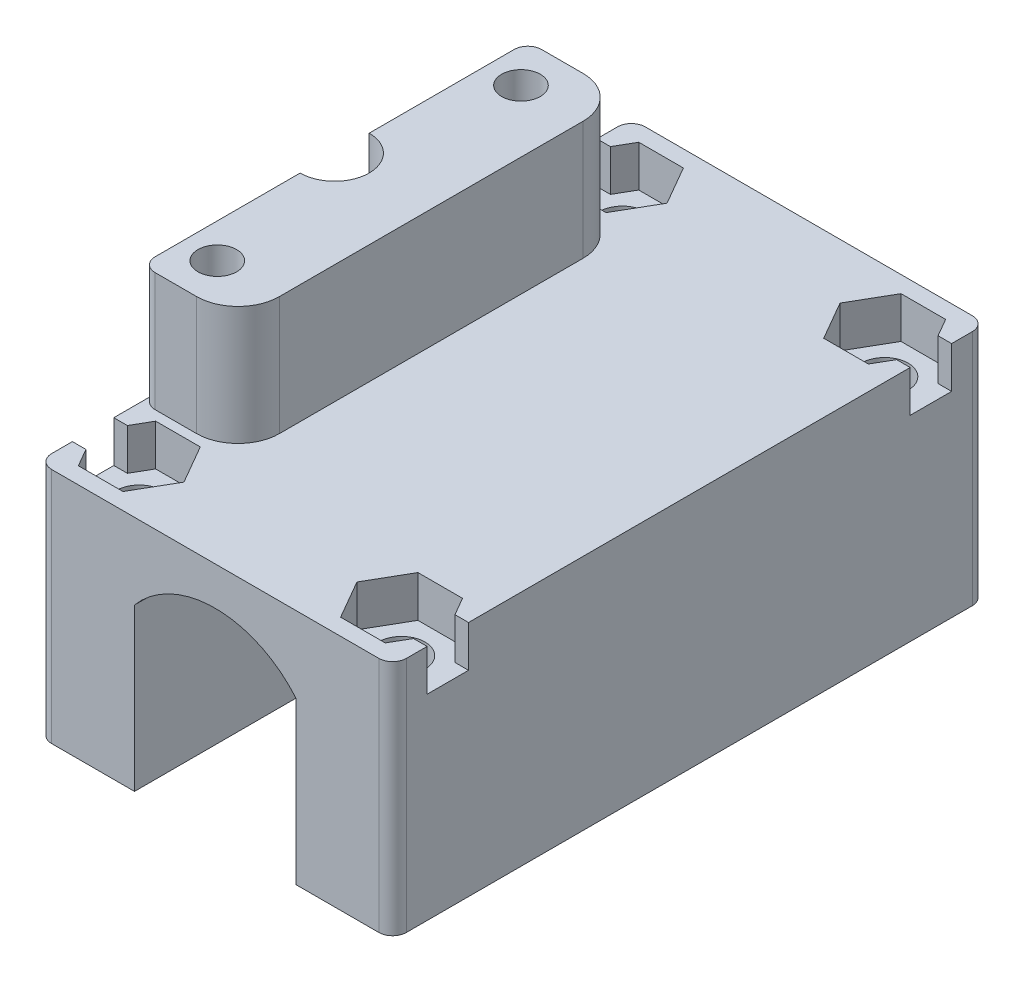
SolidWorks part; units mm, degrees
material "ABS"
ref_plane "Front" through (0, 0, 0) normal (0, 0, 1) x (1, 0, 0)
ref_plane "Top" through (0, 0, 0) normal (0, 1, 0) x (1, 0, 0)
ref_plane "Right" through (0, 0, 0) normal (1, 0, 0) x (0, 0, -1)
sketch "Эскиз1" plane through (0, 0, 0) normal (0, 0, 1) x (1, 0, 0)
  line L0 (0, 0) -> (0, 2.2539) construction
  line L1 (0, 0) -> (0, 23.5957) construction
  line L2 (5.85, 0) -> (5.85, 11.6995)
  line L3 (-12.85, 17.2) -> (12.85, 17.2)
  line L4 (12.85, 17.2) -> (12.85, 0)
  line L5 (12.85, 0) -> (5.85, 0)
  line L6 (-12.85, 0) -> (-5.85, 0)
  line L7 (-12.85, 17.2) -> (-12.85, 0)
  line L8 (-5.85, 0) -> (-5.85, 11.6995)
  arc A0 (5.85, 11.6995) -> (-5.85, 11.6995) centre (0, 6.77) ccw
  point P15 (0, 17.2)
  dimension "D3" = 6.77
  dimension "D4" = 15.3
  dimension "D1" = 11.7
  dimension "D5" = 7
  dimension "D6" = 17.2
extrude "Бобышка-Вытянуть1" add sketch "Эскиз1" along normal blind 43
sketch "Эскиз2" plane through (0, 17.2, 0) normal (0, 1, 0) x (1, 0, 0)
  line L0 (-17.85, -21.5) -> (16.0301, -21.5) construction
  line L1 (-17.85, -21.5) -> (-17.85, 1.982) construction
  line L2 (-12.85, -43) -> (-12.85, 0) construction
  line L3 (-12.85, -7.5) -> (-8.85, -7.5)
  line L4 (-5.85, -10.5) -> (-5.85, -32.5)
  line L5 (-12.85, -7.5) -> (-12.85, -19)
  line L6 (-12.85, -35.5) -> (-12.85, -24)
  line L7 (-12.85, -35.5) -> (-8.85, -35.5)
  arc A1 (-12.85, -24) -> (-12.85, -19) centre (-12.85, -21.5) ccw
  arc A2 (-8.85, -7.5) -> (-5.85, -10.5) centre (-8.85, -10.5) cw
  arc A3 (-8.85, -35.5) -> (-5.85, -32.5) centre (-8.85, -32.5) ccw
  point P21 (-5.85, -21.5)
  dimension "D5" = 5
  dimension "D6" = 3
  dimension "D1" = 5
  dimension "D7" = 14
  dimension "D8" = 7
extrude "Бобышка-Вытянуть2" add sketch "Эскиз2" along normal blind 8.6
sketch "Эскиз3" plane through (0, 25.8, 0) normal (0, 1, 0) x (1, 0, 0)
  line L0 (-12.85, -21.5) -> (0, -21.5) construction
  line L1 (-12.85, -24) -> (-12.85, -19) construction
  circle A0 centre (-10.35, -10.5) radius 1.4
  circle A1 centre (-10.35, -32.5) radius 1.4
  dimension "D3" = 2.8
  dimension "D1" = 11
  dimension "D2" = 2.5
extrude "Вырез-Вытянуть1" cut sketch "Эскиз3" against normal blind 15
sketch "Эскиз4" plane through (0, 17.2, 0) normal (0, 1, 0) x (1, 0, 0)
  line L0 (-12.85, -24) -> (-12.85, -19) construction
  circle A0 centre (-12.85, -21.5) radius 2.5
extrude "Вырез-Вытянуть2" cut sketch "Эскиз4" against normal up to surface (17.2 mm away) up to face at (-9.35, 0, 21.5)
sketch "Эскиз5" plane through (-12.85, 0, 0) normal (-1, 0, 0) x (0, 0, 1)
  line L0 (21.5, 0) -> (21.5, 28.1318) construction
  line L1 (19, 0) -> (24, 0) construction
  line L2 (24, 0) -> (24, 10)
  line L3 (43, 0) -> (24, 0) construction
  line L4 (24, 10) -> (19, 10)
  line L5 (19, 0) -> (19, 10)
  line L6 (19, 0) -> (24, 0)
  line L7 (24, 0) -> (23.971, 0.0167)
  point P11 (21.5, 10)
  dimension "D1" = 5
  dimension "D2" = 10
extrude "Вырез-Вытянуть3" cut sketch "Эскиз5" against normal blind 15
sketch "Эскиз6" plane through (0, 0, 0) normal (0, -1, 0) x (1, 0, 0)
  line L0 (0, 0) -> (0, 48.9156) construction
  line L1 (12.85, 21.5) -> (-29.1881, 21.5) construction
  line L2 (12.85, 43) -> (12.85, 0) construction
  circle A0 centre (9.5, 39) radius 1.7
  circle A1 centre (-9.5, 39) radius 1.7
  circle A2 centre (9.5, 4) radius 1.7
  circle A3 centre (-9.5, 4) radius 1.7
  dimension "D1" = 3.4
  dimension "D2" = 19
  dimension "D3" = 17.5
extrude "Вырез-Вытянуть4" cut sketch "Эскиз6" against normal blind 20
sketch "Эскиз7" plane through (0, 17.2, 0) normal (0, 1, 0) x (1, 0, 0)
  line L0 (-9.5, -4) -> (-15.0428, -4) construction
  line L1 (0, 0) -> (0, -46.2924) construction
  line L2 (-11.8671, -5.5) -> (-11.1166, -6.8)
  line L3 (-11.1166, -6.8) -> (-7.8834, -6.8)
  line L4 (-7.8834, -6.8) -> (-6.2668, -4)
  line L5 (-6.2668, -4) -> (-7.8834, -1.2)
  line L6 (-7.8834, -1.2) -> (-11.1166, -1.2)
  line L7 (-11.1166, -1.2) -> (-11.8671, -2.5)
  line L8 (-15.0428, -2.5) -> (-11.8643, -2.5)
  line L9 (-15.0428, -5.5) -> (-11.8643, -5.5)
  line L10 (-15.0428, -2.5) -> (-15.0428, -5.5)
  line L11 (-15.0428, -2.5) -> (-11.8643, -2.5)
  line L12 (-15.0428, -5.5) -> (-11.8643, -5.5)
  line L13 (-11.1166, -6.8) -> (-11.8671, -5.5)
  line L14 (-7.8834, -6.8) -> (-11.1166, -6.8)
  line L15 (-6.2668, -4) -> (-7.8834, -6.8)
  line L16 (-7.8834, -1.2) -> (-6.2668, -4)
  line L17 (-11.1166, -1.2) -> (-7.8834, -1.2)
  line L18 (-11.8671, -2.5) -> (-11.1166, -1.2)
  line L19 (-11.8671, -5.5) -> (-11.1166, -6.8)
  line L20 (-11.1166, -6.8) -> (-7.8834, -6.8)
  line L21 (-12.85, -21.5) -> (15.6837, -21.5) construction
  line L22 (-7.8834, -6.8) -> (-6.2668, -4)
  line L23 (-6.2668, -4) -> (-7.8834, -1.2)
  line L24 (-7.8834, -1.2) -> (-11.1166, -1.2)
  line L25 (-11.1166, -1.2) -> (-11.8671, -2.5)
  line L26 (-15.0428, -2.5) -> (-11.8643, -2.5)
  line L27 (-15.0428, -5.5) -> (-11.8643, -5.5)
  line L28 (-15.0428, -2.5) -> (-11.8643, -2.5)
  line L29 (-15.0428, -5.5) -> (-11.8643, -5.5)
  line L30 (-11.1166, -6.8) -> (-11.8671, -5.5)
  line L31 (-7.8834, -6.8) -> (-11.1166, -6.8)
  line L32 (-6.2668, -4) -> (-7.8834, -6.8)
  line L33 (-7.8834, -1.2) -> (-6.2668, -4)
  line L34 (-11.1166, -1.2) -> (-7.8834, -1.2)
  line L35 (-11.8671, -2.5) -> (-11.1166, -1.2)
  line L36 (11.1166, -1.2) -> (11.8671, -2.5)
  line L37 (7.8834, -1.2) -> (11.1166, -1.2)
  line L38 (6.2668, -4) -> (7.8834, -1.2)
  line L39 (7.8834, -6.8) -> (6.2668, -4)
  line L40 (11.1166, -6.8) -> (7.8834, -6.8)
  line L41 (11.8671, -5.5) -> (11.1166, -6.8)
  line L42 (15.0428, -5.5) -> (11.8643, -5.5)
  line L43 (15.0428, -2.5) -> (15.0428, -5.5)
  line L44 (15.0428, -2.5) -> (11.8643, -2.5)
  line L45 (15.0428, -5.5) -> (11.8643, -5.5)
  line L46 (15.0428, -2.5) -> (11.8643, -2.5)
  line L47 (11.8671, -2.5) -> (11.1166, -1.2)
  line L48 (11.1166, -1.2) -> (7.8834, -1.2)
  line L49 (7.8834, -1.2) -> (6.2668, -4)
  line L50 (6.2668, -4) -> (7.8834, -6.8)
  line L51 (7.8834, -6.8) -> (11.1166, -6.8)
  line L52 (11.1166, -6.8) -> (11.8671, -5.5)
  line L53 (-11.8671, -5.5) -> (-11.1166, -6.8)
  line L54 (-11.1166, -6.8) -> (-7.8834, -6.8)
  line L55 (-7.8834, -6.8) -> (-6.2668, -4)
  line L56 (-6.2668, -4) -> (-7.8834, -1.2)
  line L57 (-7.8834, -1.2) -> (-11.1166, -1.2)
  line L58 (-11.1166, -1.2) -> (-11.8671, -2.5)
  line L59 (-15.0428, -2.5) -> (-11.8643, -2.5)
  line L60 (-15.0428, -5.5) -> (-11.8643, -5.5)
  line L61 (-15.0428, -2.5) -> (-11.8643, -2.5)
  line L62 (-15.0428, -5.5) -> (-11.8643, -5.5)
  line L63 (-11.1166, -6.8) -> (-11.8671, -5.5)
  line L64 (-7.8834, -6.8) -> (-11.1166, -6.8)
  line L65 (-6.2668, -4) -> (-7.8834, -6.8)
  line L66 (-7.8834, -1.2) -> (-6.2668, -4)
  line L67 (-11.1166, -1.2) -> (-7.8834, -1.2)
  line L68 (-11.8671, -2.5) -> (-11.1166, -1.2)
  line L69 (-11.8671, -5.5) -> (-11.1166, -6.8)
  line L70 (-11.1166, -6.8) -> (-7.8834, -6.8)
  line L71 (-7.8834, -6.8) -> (-6.2668, -4)
  line L72 (-6.2668, -4) -> (-7.8834, -1.2)
  line L73 (-7.8834, -1.2) -> (-11.1166, -1.2)
  line L74 (-11.1166, -1.2) -> (-11.8671, -2.5)
  line L75 (-15.0428, -2.5) -> (-11.8643, -2.5)
  line L76 (-15.0428, -5.5) -> (-11.8643, -5.5)
  line L77 (-15.0428, -2.5) -> (-11.8643, -2.5)
  line L78 (-15.0428, -5.5) -> (-11.8643, -5.5)
  line L79 (-11.1166, -6.8) -> (-11.8671, -5.5)
  line L80 (-7.8834, -6.8) -> (-11.1166, -6.8)
  line L81 (-6.2668, -4) -> (-7.8834, -6.8)
  line L82 (-7.8834, -1.2) -> (-6.2668, -4)
  line L83 (-11.1166, -1.2) -> (-7.8834, -1.2)
  line L84 (-11.8671, -2.5) -> (-11.1166, -1.2)
  line L85 (0, -43) -> (0, 3.2924) construction
  line L86 (-9.5, -39) -> (-15.0428, -39) construction
  line L87 (-11.8671, -40.5) -> (-11.1166, -41.8)
  line L88 (-11.1166, -41.8) -> (-7.8834, -41.8)
  line L89 (-7.8834, -41.8) -> (-6.2668, -39)
  line L90 (-6.2668, -39) -> (-7.8834, -36.2)
  line L91 (-7.8834, -36.2) -> (-11.1166, -36.2)
  line L92 (-11.1166, -36.2) -> (-11.8671, -37.5)
  line L93 (-15.0428, -37.5) -> (-11.8643, -37.5)
  line L94 (-15.0428, -40.5) -> (-11.8643, -40.5)
  line L95 (-15.0428, -37.5) -> (-11.8643, -37.5)
  line L96 (-15.0428, -40.5) -> (-11.8643, -40.5)
  line L97 (-11.1166, -41.8) -> (-11.8671, -40.5)
  line L98 (-7.8834, -41.8) -> (-11.1166, -41.8)
  line L99 (-6.2668, -39) -> (-7.8834, -41.8)
  line L100 (-7.8834, -36.2) -> (-6.2668, -39)
  line L101 (-11.1166, -36.2) -> (-7.8834, -36.2)
  line L102 (-11.8671, -37.5) -> (-11.1166, -36.2)
  line L103 (-11.8671, -40.5) -> (-11.1166, -41.8)
  line L104 (-11.1166, -41.8) -> (-7.8834, -41.8)
  line L105 (-7.8834, -41.8) -> (-6.2668, -39)
  line L106 (-6.2668, -39) -> (-7.8834, -36.2)
  line L107 (-7.8834, -36.2) -> (-11.1166, -36.2)
  line L108 (-11.1166, -36.2) -> (-11.8671, -37.5)
  line L109 (-15.0428, -37.5) -> (-11.8643, -37.5)
  line L110 (-15.0428, -40.5) -> (-11.8643, -40.5)
  line L111 (-15.0428, -37.5) -> (-11.8643, -37.5)
  line L112 (-15.0428, -40.5) -> (-11.8643, -40.5)
  line L113 (-11.1166, -41.8) -> (-11.8671, -40.5)
  line L114 (-7.8834, -41.8) -> (-11.1166, -41.8)
  line L115 (-6.2668, -39) -> (-7.8834, -41.8)
  line L116 (-7.8834, -36.2) -> (-6.2668, -39)
  line L117 (-11.1166, -36.2) -> (-7.8834, -36.2)
  line L118 (-11.8671, -37.5) -> (-11.1166, -36.2)
  line L119 (11.1166, -36.2) -> (11.8671, -37.5)
  line L120 (7.8834, -36.2) -> (11.1166, -36.2)
  line L121 (6.2668, -39) -> (7.8834, -36.2)
  line L122 (7.8834, -41.8) -> (6.2668, -39)
  line L123 (11.1166, -41.8) -> (7.8834, -41.8)
  line L124 (11.8671, -40.5) -> (11.1166, -41.8)
  line L125 (15.0428, -40.5) -> (11.8643, -40.5)
  line L126 (15.0428, -37.5) -> (11.8643, -37.5)
  line L127 (15.0428, -40.5) -> (11.8643, -40.5)
  line L128 (15.0428, -40.5) -> (15.0428, -37.5)
  line L129 (15.0428, -37.5) -> (11.8643, -37.5)
  line L130 (11.8671, -37.5) -> (11.1166, -36.2)
  line L131 (11.1166, -36.2) -> (7.8834, -36.2)
  line L132 (7.8834, -36.2) -> (6.2668, -39)
  line L133 (6.2668, -39) -> (7.8834, -41.8)
  line L134 (7.8834, -41.8) -> (11.1166, -41.8)
  line L135 (11.1166, -41.8) -> (11.8671, -40.5)
  line L136 (-11.8671, -40.5) -> (-11.1166, -41.8)
  line L137 (-11.1166, -41.8) -> (-7.8834, -41.8)
  line L138 (-7.8834, -41.8) -> (-6.2668, -39)
  line L139 (-6.2668, -39) -> (-7.8834, -36.2)
  line L140 (-7.8834, -36.2) -> (-11.1166, -36.2)
  line L141 (-11.1166, -36.2) -> (-11.8671, -37.5)
  line L142 (-15.0428, -37.5) -> (-11.8643, -37.5)
  line L143 (-15.0428, -40.5) -> (-11.8643, -40.5)
  line L144 (-15.0428, -37.5) -> (-11.8643, -37.5)
  line L145 (-15.0428, -40.5) -> (-11.8643, -40.5)
  line L146 (-11.1166, -41.8) -> (-11.8671, -40.5)
  line L147 (-7.8834, -41.8) -> (-11.1166, -41.8)
  line L148 (-6.2668, -39) -> (-7.8834, -41.8)
  line L149 (-7.8834, -36.2) -> (-6.2668, -39)
  line L150 (-11.1166, -36.2) -> (-7.8834, -36.2)
  line L151 (-11.8671, -37.5) -> (-11.1166, -36.2)
  line L152 (-11.8671, -40.5) -> (-11.1166, -41.8)
  line L153 (-11.1166, -41.8) -> (-7.8834, -41.8)
  line L154 (-7.8834, -41.8) -> (-6.2668, -39)
  line L155 (-6.2668, -39) -> (-7.8834, -36.2)
  line L156 (-7.8834, -36.2) -> (-11.1166, -36.2)
  line L157 (-11.1166, -36.2) -> (-11.8671, -37.5)
  line L158 (-15.0428, -37.5) -> (-11.8643, -37.5)
  line L159 (-15.0428, -40.5) -> (-11.8643, -40.5)
  line L160 (-15.0428, -40.5) -> (-15.0428, -37.5)
  line L161 (-15.0428, -37.5) -> (-11.8643, -37.5)
  line L162 (-15.0428, -40.5) -> (-11.8643, -40.5)
  line L163 (-11.1166, -41.8) -> (-11.8671, -40.5)
  line L164 (-7.8834, -41.8) -> (-11.1166, -41.8)
  line L165 (-6.2668, -39) -> (-7.8834, -41.8)
  line L166 (-7.8834, -36.2) -> (-6.2668, -39)
  line L167 (-11.1166, -36.2) -> (-7.8834, -36.2)
  line L168 (-11.8671, -37.5) -> (-11.1166, -36.2)
  circle A0 centre (-9.5, -4) radius 2.8 construction
  circle A1 centre (-9.5, -39) radius 2.8 construction
  dimension "D1" = 5.6
  dimension "D2" = 3
extrude "Вырез-Вытянуть5" cut sketch "Эскиз7" against normal blind 3
fillet "Скругление1" radius 3 2 edges at (-5.85, 5, 19) (-5.85, 5, 24)
fillet "Скругление2" radius 1 6 edges at (12.85, 8.6, 0) (-12.85, 8.6, 0) (12.85, 8.6, 43) (-12.85, 8.6, 43)
